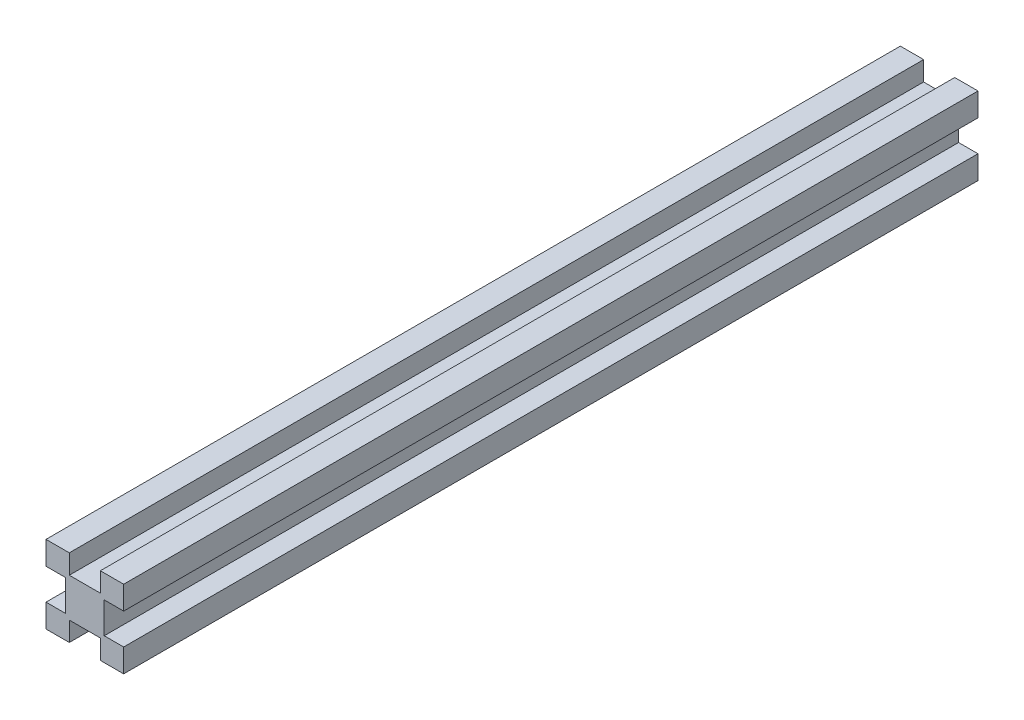
SolidWorks part; units mm, degrees
ref_plane "Alzado" through (0, 0, 0) normal (0, 0, 1) x (1, 0, 0)
ref_plane "Planta" through (0, 0, 0) normal (0, 1, 0) x (1, 0, 0)
ref_plane "Vista lateral" through (0, 0, 0) normal (1, 0, 0) x (0, 0, -1)
sketch "Croquis1" plane through (0, 0, 0) normal (0, 0, 1) x (1, 0, 0)
  line L1 (-23.5326, 14.5417) -> (-3.5326, 14.5417)
  line L2 (-23.5326, 14.5417) -> (-23.5326, -5.4583)
  line L3 (-23.5326, -5.4583) -> (-3.5326, -5.4583)
  line L4 (-3.5326, 14.5417) -> (-3.5326, -5.4583)
  line L5 (-23.5326, 14.5417) -> (-3.5326, -5.4583) construction
  line L6 (-23.5326, -5.4583) -> (-3.5326, 14.5417) construction
  point P0 (-13.5326, 4.5417)
  dimension "D1" = 20
extrude "Saliente-Extruir1" add sketch "Croquis1" along normal blind 220
sketch "Croquis2" plane through (0, 0, 220) normal (0, 0, 1) x (1, 0, 0)
  line L0 (-23.5326, 4.5417) -> (-3.5326, 4.5417) construction
  line L1 (-3.5326, 14.5417) -> (-23.5326, 14.5417) construction
  line L2 (-13.5326, 9.5417) -> (-17.5326, 9.5417)
  line L3 (-13.5326, 9.5417) -> (-9.5326, 9.5417)
  line L4 (-17.5326, 9.5417) -> (-17.5326, 14.5417)
  line L5 (-9.5326, 9.5417) -> (-9.5326, 14.5417)
  line L6 (-17.5326, 14.5417) -> (-9.5326, 14.5417)
  line L7 (-23.5326, 14.5417) -> (-23.5326, -5.4583) construction
  line L8 (-3.5326, -5.4583) -> (-3.5326, 14.5417) construction
  line L9 (-13.5326, 14.5417) -> (-13.5326, -5.4583) construction
  line L10 (-23.5326, -5.4583) -> (-3.5326, -5.4583) construction
  line L11 (-9.5326, -0.4583) -> (-9.5326, -5.4583)
  line L12 (-13.5326, -0.4583) -> (-9.5326, -0.4583)
  line L13 (-13.5326, -0.4583) -> (-17.5326, -0.4583)
  line L14 (-17.5326, -5.4583) -> (-9.5326, -5.4583)
  line L15 (-17.5326, -0.4583) -> (-17.5326, -5.4583)
  line L16 (-23.5326, 4.5417) -> (-23.5326, 8.5417)
  line L17 (-23.5326, 8.5417) -> (-18.5326, 8.5417)
  line L18 (-18.5326, 8.5417) -> (-18.5326, 0.5417)
  line L19 (-18.5326, 0.5417) -> (-23.5326, 0.5417)
  line L20 (-23.5326, 0.5417) -> (-23.5326, 4.5417)
  line L21 (-8.5326, 8.5417) -> (-8.5326, 0.5417)
  line L22 (-8.5326, 0.5417) -> (-3.5326, 0.5417)
  line L23 (-3.5326, 0.5417) -> (-3.5326, 4.5417)
  line L24 (-3.5326, 4.5417) -> (-3.5326, 8.5417)
  line L25 (-3.5326, 8.5417) -> (-8.5326, 8.5417)
  dimension "D1" = 4
  dimension "D2" = 5
extrude "Cortar-Extruir1" cut sketch "Croquis2" against normal blind 320
